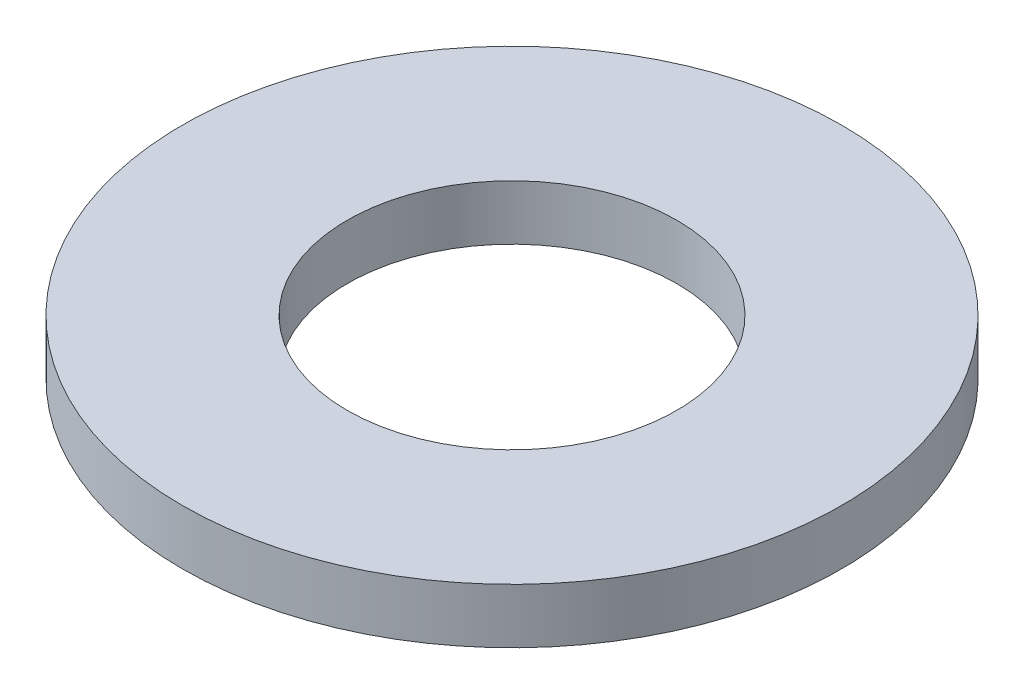
SolidWorks part; units mm, degrees
material "AISI 304"
ref_plane "前视基准面" through (0, 0, 0) normal (0, 0, 1) x (1, 0, 0)
ref_plane "上视基准面" through (0, 0, 0) normal (0, 1, 0) x (1, 0, 0)
ref_plane "右视基准面" through (0, 0, 0) normal (1, 0, 0) x (0, 0, -1)
other "Configuration Table"
sketch "草图1" plane through (0, 0, 0) normal (0, 1, 0) x (1, 0, 0)
  circle A0 centre (0, 0) radius 3
  circle A1 centre (0, 0) radius 1.5
  dimension "D1" = 3
  dimension "D2" = 6
extrude "凸台-拉伸1" add sketch "草图1" along normal blind 0.5
